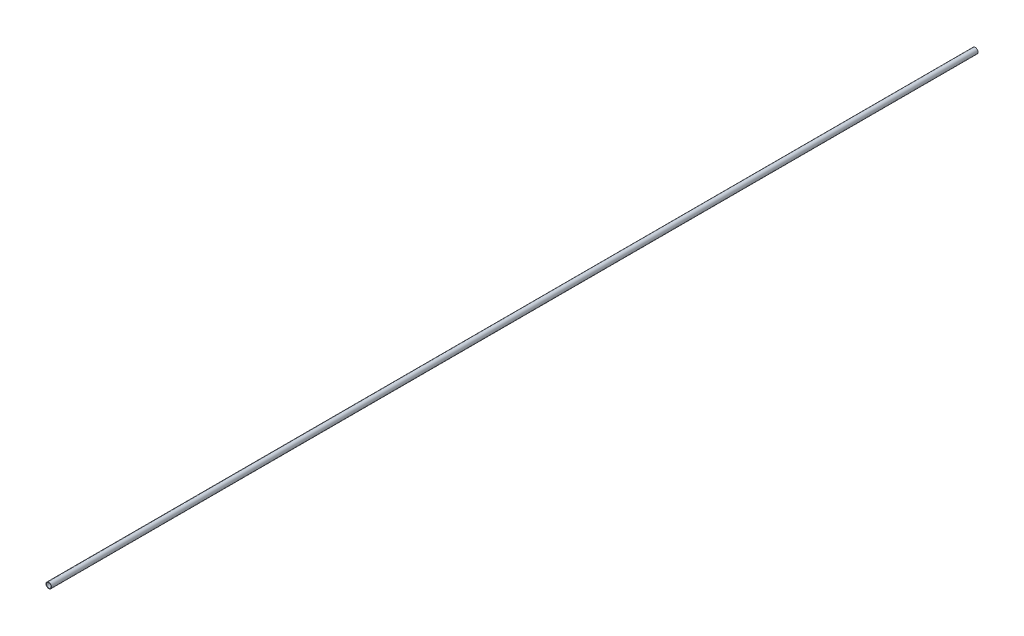
SolidWorks part; units mm, degrees
material "Плетеная трубка"
ref_plane "Front Plane" through (0, 0, 0) normal (0, 0, 1) x (1, 0, 0)
ref_plane "Top Plane" through (0, 0, 0) normal (0, 1, 0) x (1, 0, 0)
ref_plane "Right Plane" through (0, 0, 0) normal (1, 0, 0) x (0, 0, -1)
sketch "Sketch1" plane through (0, 0, 0) normal (0, 0, 1) x (1, 0, 0)
  circle A0 centre (0, 0) radius 3
  dimension "D1" = 6
extrude "Boss-Extrude1" add sketch "Sketch1" along normal mid plane 1000
shell "Shell1" thickness 0.5
